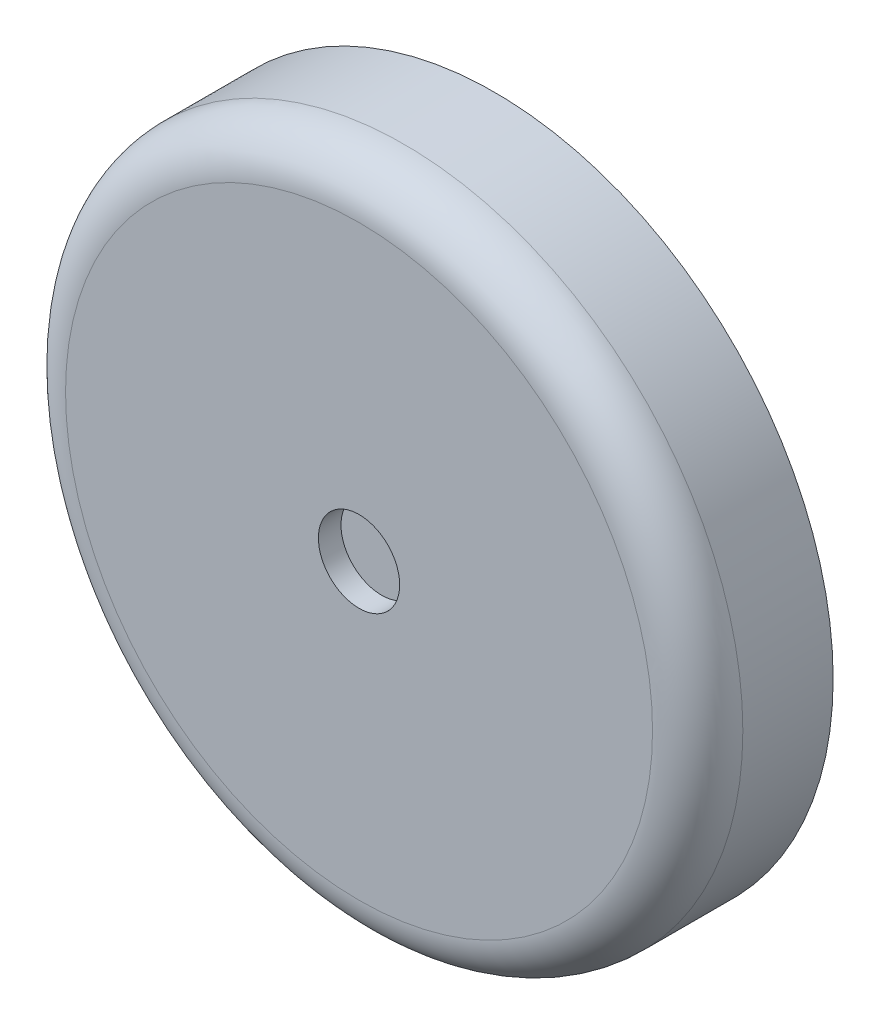
SolidWorks part; units mm, degrees
ref_plane "Front Plane" through (0, 0, 0) normal (0, 0, 1) x (1, 0, 0)
ref_plane "Top Plane" through (0, 0, 0) normal (0, 1, 0) x (1, 0, 0)
ref_plane "Right Plane" through (0, 0, 0) normal (1, 0, 0) x (0, 0, -1)
sketch "Sketch1" plane through (0, 0, 0) normal (0, 0, 1) x (1, 0, 0)
  circle A0 centre (0, 0) radius 15
extrude "Boss-Extrude1" add sketch "Sketch1" along normal blind 6
fillet "Fillet1" radius 2 1 edges at (15, 0, 6)
sketch "Sketch2" plane through (0, 0, 0) normal (0, 0, -1) x (-1, 0, 0)
  circle A0 centre (0, 0) radius 13.5
extrude "Cut-Extrude1" cut sketch "Sketch2" against normal blind 4 contours A0
fillet "Fillet2" radius 2 1 edges at (-13.5, 0, 4)
sketch "Sketch4" plane through (0, 0, 6) normal (0, 0, 1) x (1, 0, 0)
  circle A0 centre (0, 0) radius 1.8
extrude "Cut-Extrude3" cut sketch "Sketch4" against normal blind 1 contours A0
